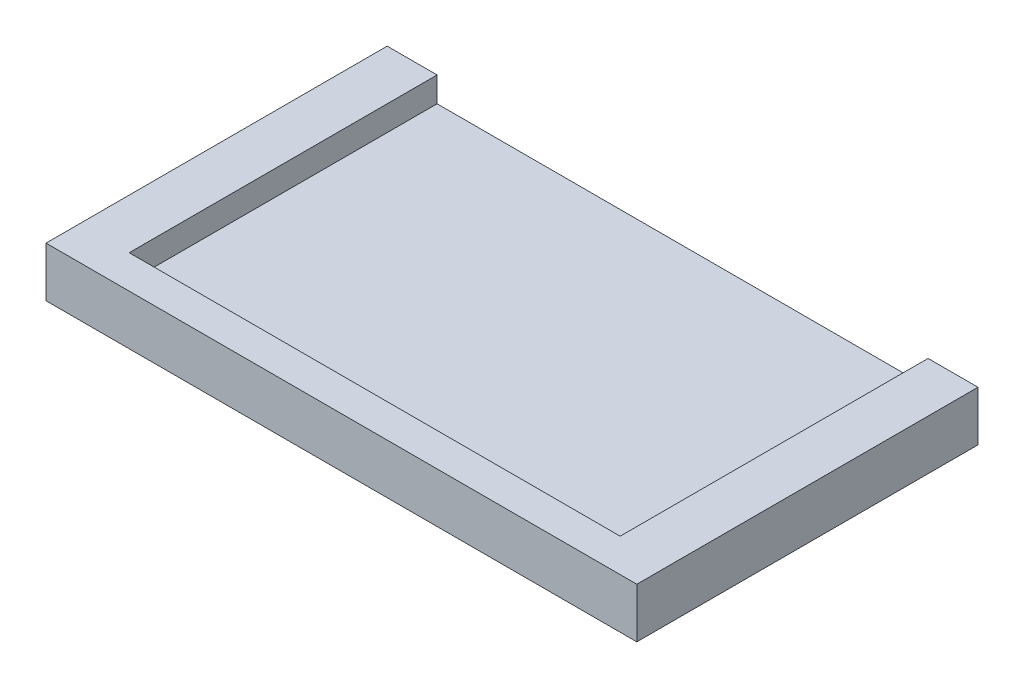
SolidWorks part; units mm, degrees
ref_plane "Front Plane" through (0, 0, 0) normal (0, 0, 1) x (1, 0, 0)
ref_plane "Top Plane" through (0, 0, 0) normal (0, 1, 0) x (1, 0, 0)
ref_plane "Right Plane" through (0, 0, 0) normal (1, 0, 0) x (0, 0, -1)
sketch "Sketch1" plane through (0, 0, 0) normal (0, 1, 0) x (1, 0, 0)
  line L1 (-17.75, 10.25) -> (17.75, 10.25)
  line L2 (-17.75, 10.25) -> (-17.75, -10.25)
  line L3 (-17.75, -10.25) -> (17.75, -10.25)
  line L4 (17.75, 10.25) -> (17.75, -10.25)
  dimension "D1" = 35.5
  dimension "D2" = 20.5
  dimension "D3" = 10.25
  dimension "D4" = 17.75
extrude "Boss-Extrude1" add sketch "Sketch1" along normal blind 1.5
sketch "Sketch2" plane through (0, 1.5, 0) normal (0, 1, 0) x (1, 0, 0)
  line L0 (17.75, 10.25) -> (14.75, 10.25)
  line L1 (17.75, 10.25) -> (-17.75, 10.25) construction
  line L2 (14.75, 10.25) -> (14.75, -8.25)
  line L3 (14.75, -8.25) -> (-14.75, -8.25)
  line L4 (-14.75, -8.25) -> (-14.75, 10.25)
  line L5 (-14.75, 10.25) -> (-17.75, 10.25)
  line L6 (-17.75, 10.25) -> (-17.75, -10.25)
  line L7 (-17.75, -10.25) -> (17.75, -10.25)
  line L8 (17.75, -10.25) -> (17.75, 10.25)
  dimension "D1" = 3
  dimension "D2" = 3
  dimension "D3" = 2
extrude "Boss-Extrude2" add sketch "Sketch2" along normal blind 1.5
sketch "Sketch4" plane through (0, 1.5, 0) normal (0, 1, 0) x (1, 0, 0)
  line L0 (-8.6605, -8.25) -> (-8.6605, -1.6011)
  line L1 (14.75, -8.25) -> (-14.75, -8.25) construction
  line L2 (-8.6605, -1.6011) -> (-9.6066, -1.6011)
  line L3 (-9.6066, -1.6011) -> (-9.6066, -0.5822)
  line L4 (-9.6066, -0.5822) -> (-8.6605, -0.5822)
  line L5 (-8.6605, -0.5822) -> (-8.6605, 2.438)
  line L6 (-8.6605, 2.438) -> (8.3694, 2.438)
  line L7 (8.3694, 2.438) -> (8.3694, -0.5822)
  line L8 (8.3694, -0.5822) -> (9.643, -0.5822)
  line L9 (9.643, -0.5822) -> (9.643, -1.6011)
